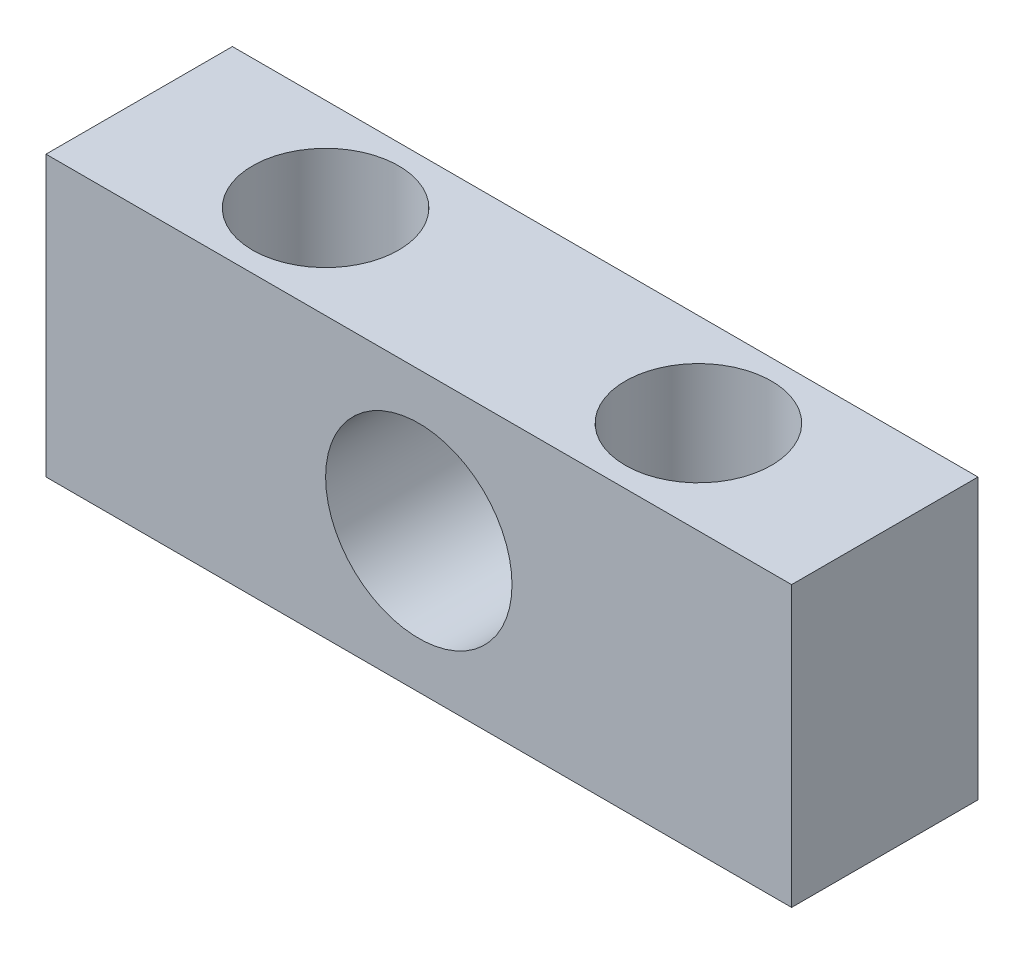
SolidWorks part; units mm, degrees
ref_plane "Front Plane" through (0, 0, 0) normal (0, 0, 1) x (1, 0, 0)
ref_plane "Top Plane" through (0, 0, 0) normal (0, 1, 0) x (1, 0, 0)
ref_plane "Right Plane" through (0, 0, 0) normal (1, 0, 0) x (0, 0, -1)
sketch "Sketch1" plane through (0, 0, 0) normal (0, 0, 1) x (1, 0, 0)
  line L1 (-12.7, -4.7625) -> (12.7, -4.7625)
  line L2 (-12.7, -4.7625) -> (-12.7, 4.7625)
  line L3 (-12.7, 4.7625) -> (12.7, 4.7625)
  line L4 (12.7, -4.7625) -> (12.7, 4.7625)
  line L5 (-12.7, -4.7625) -> (12.7, 4.7625) construction
  line L6 (-12.7, 4.7625) -> (12.7, -4.7625) construction
  circle A0 centre (0, 0) radius 3.175
  point P0 (0, 0)
  point P8 (0, 4.7625)
  dimension "D1" = 6.35
  dimension "D2" = 9.525
  dimension "D3" = 25.4
extrude "Boss-Extrude1" add sketch "Sketch1" along normal mid plane 6.35
sketch "Sketch2" plane through (0, 0, 0) normal (0, 1, 0) x (1, 0, 0)
  line L0 (-12.7, -3.175) -> (-12.7, 3.175) construction
  circle A0 centre (6.35, 0) radius 2.4892
  circle A1 centre (-6.35, 0) radius 2.4892
  point P6 (-12.7, 0)
  dimension "D1" = 4.9784
  dimension "D2" = 12.7
  dimension "D3" = 6.35
extrude "Cut-Extrude1" cut sketch "Sketch2" against normal through all both and the other way through all
